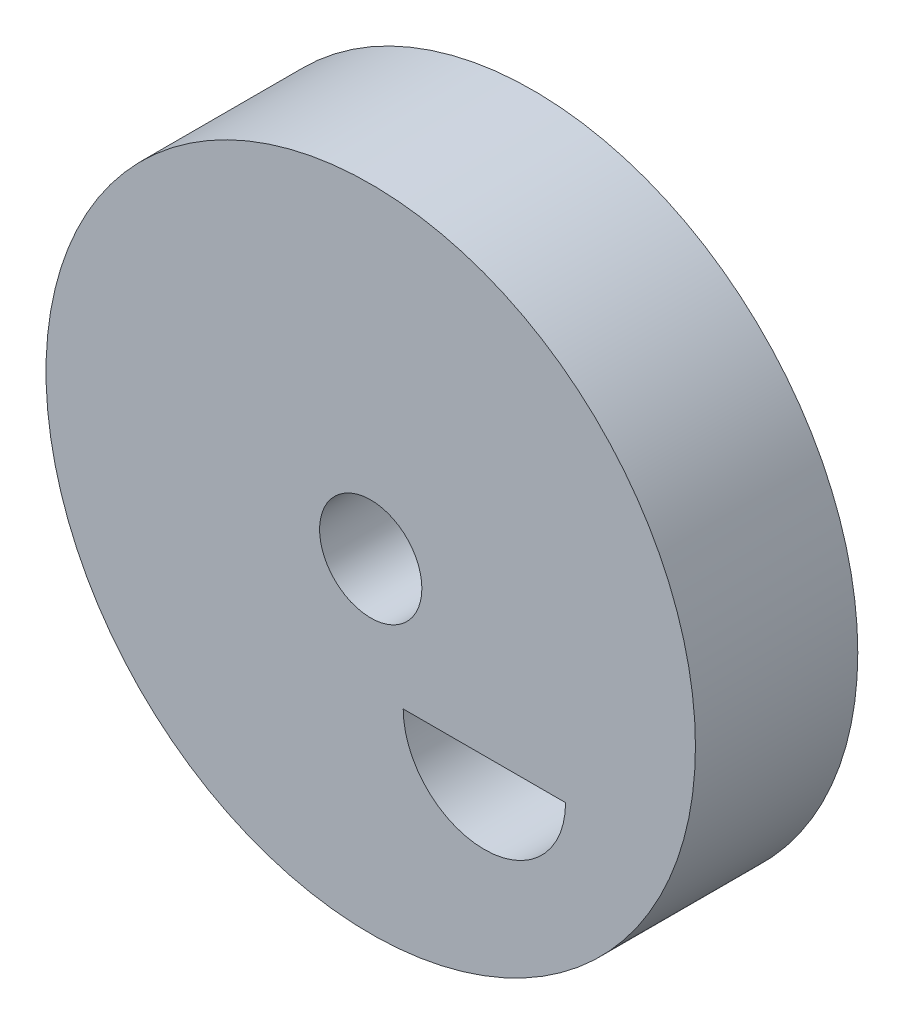
SolidWorks part; units mm, degrees
ref_plane "Front Plane" through (0, 0, 0) normal (0, 0, 1) x (1, 0, 0)
ref_plane "Top Plane" through (0, 0, 0) normal (0, 1, 0) x (1, 0, 0)
ref_plane "Right Plane" through (0, 0, 0) normal (1, 0, 0) x (0, 0, -1)
sketch "Sketch1" plane through (0, 0, 0) normal (0, 0, 1) x (1, 0, 0)
  circle A0 centre (0, 0) radius 25.4
  circle A1 centre (0, 0) radius 4
  dimension "D1" = 8
  dimension "D2" = 50.8
extrude "Boss-Extrude1" add sketch "Sketch1" along normal blind 12.7
sketch "Sketch2" plane through (0, 0, 0) normal (0, 0, 1) x (1, 0, 0)
  circle A0 centre (8.89, -8.89) radius 6.35
  point P5 (2.9917, -2.6551)
  dimension "D3" = 12.7
  dimension "D1" = 8.89
  dimension "D2" = 8.89
extrude "Cut-Extrude1" cut sketch "Sketch2" along normal blind 6.35
sketch "Sketch3" plane through (0, 0, 0) normal (0, 0, 1) x (1, 0, 0)
  line L0 (2.54, -8.89) -> (15.24, -8.89)
  arc A0 (2.54, -8.89) -> (15.24, -8.89) centre (8.89, -8.89) ccw
  point P3 (14.9681, -7.0518)
  point P4 (15.0487, -10.4368)
  point P6 (0, 0)
  point P7 (15.24, -8.89)
  dimension "D1" = 6.35
  dimension "D2" = 8.89
extrude "Cut-Extrude2" cut sketch "Sketch3" along normal up to surface (12.7 mm away) up to face at (25.4, 0, 12.7)
